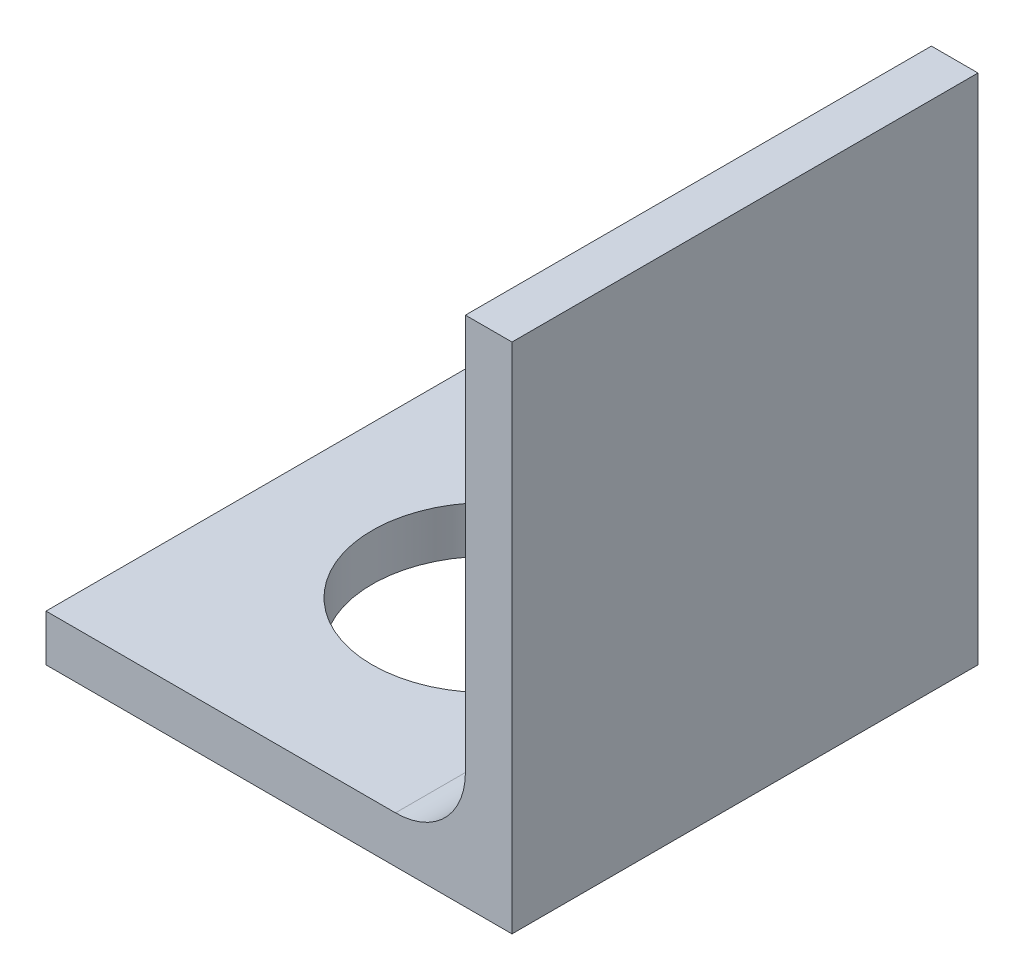
SolidWorks part; units mm, degrees
ref_plane "Front Plane" through (0, 0, 0) normal (0, 0, 1) x (1, 0, 0)
ref_plane "Top Plane" through (0, 0, 0) normal (0, 1, 0) x (1, 0, 0)
ref_plane "Right Plane" through (0, 0, 0) normal (1, 0, 0) x (0, 0, -1)
sketch "Sketch1" plane through (0, 0, 0) normal (0, 0, 1) x (1, 0, 0)
  line L1 (0, 0) -> (20, 0)
  line L2 (0, 0) -> (0, -2)
  line L3 (0, -2) -> (20, -2)
  line L4 (20, 0) -> (20, -2)
  dimension "D1" = 2
  dimension "D2" = 20
extrude "Boss-Extrude1" add sketch "Sketch1" along normal blind 20
sketch "Sketch2" plane through (0, 0, 0) normal (0, 1, 0) x (1, 0, 0)
  line L0 (20, -20) -> (0, -20) construction
  line L1 (20, 0) -> (18, 0)
  line L2 (20, 0) -> (20, -20)
  line L3 (20, -20) -> (18, -20)
  line L4 (18, 0) -> (18, -20)
  dimension "D1" = 2
extrude "Boss-Extrude2" add sketch "Sketch2" along normal blind 20
sketch "Sketch3" plane through (0, 0, 0) normal (0, 1, 0) x (1, 0, 0)
  line L0 (18, 0) -> (0, -20)
  circle A0 centre (9, -10) radius 5
  dimension "D1" = 10
extrude "Cut-Extrude1" cut sketch "Sketch3" against normal blind 30 contours A0
fillet "Fillet1" radius 3 1 edges at (18, 0, 10)
